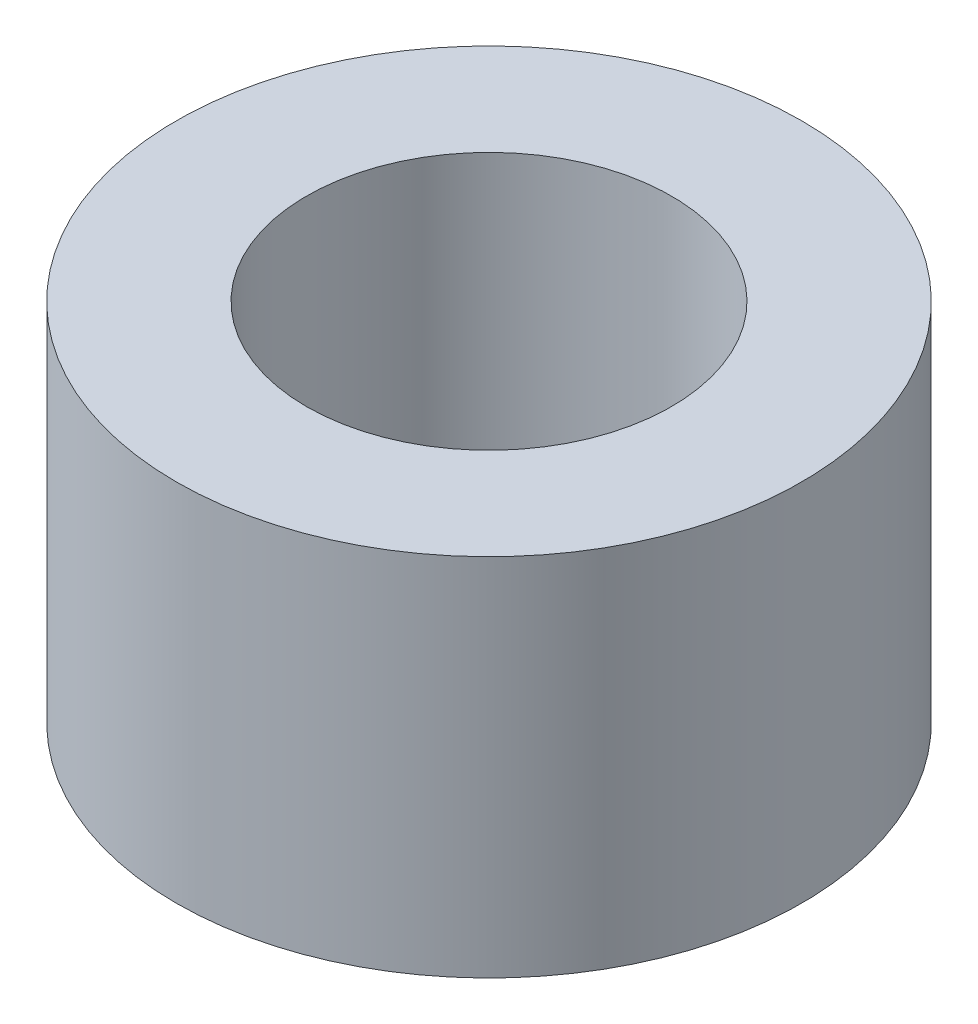
SolidWorks part; units mm, degrees
ref_plane "Front Plane" through (0, 0, 0) normal (0, 0, 1) x (1, 0, 0)
ref_plane "Top Plane" through (0, 0, 0) normal (0, 1, 0) x (1, 0, 0)
ref_plane "Right Plane" through (0, 0, 0) normal (1, 0, 0) x (0, 0, -1)
sketch "Sketch1" plane through (0, 0, 0) normal (0, 1, 0) x (1, 0, 0)
  circle A0 centre (0, 0) radius 3
  circle A1 centre (0, 0) radius 1.75
  dimension "D1" = 3.5
  dimension "D2" = 6
extrude "Boss-Extrude1" add sketch "Sketch1" along normal blind 3.5
